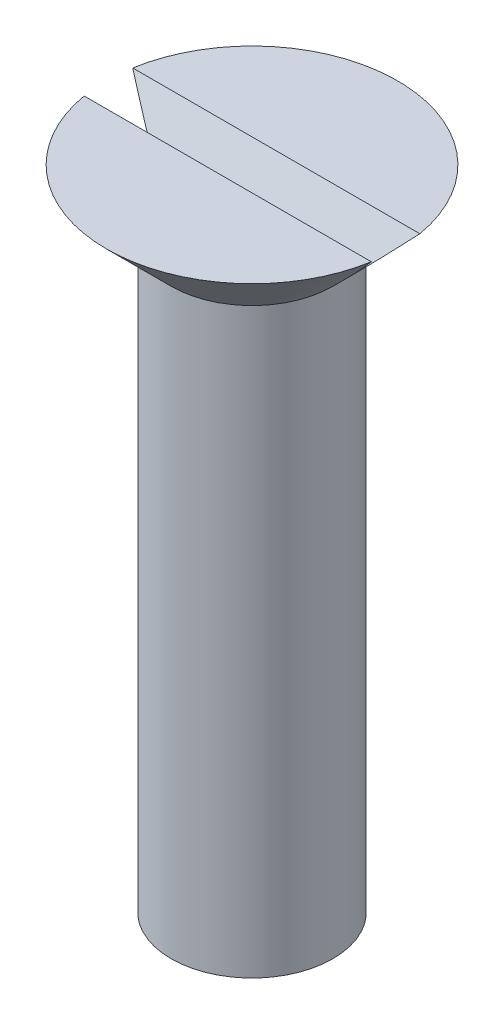
SolidWorks part; units mm, degrees
ref_plane "Front Plane" through (0, 0, 0) normal (0, 0, 1) x (1, 0, 0)
ref_plane "Top Plane" through (0, 0, 0) normal (0, 1, 0) x (1, 0, 0)
ref_plane "Right Plane" through (0, 0, 0) normal (1, 0, 0) x (0, 0, -1)
sketch "Sketch1" plane through (0, 0, 0) normal (0, 0, 1) x (1, 0, 0)
  line L0 (0, 45.5211) -> (0, -52.2099) construction
  line L1 (0, 35.1163) -> (4.5, 35.1163)
  line L2 (4.5, 35.1163) -> (2.5, 33.1163)
  line L3 (2.5, 33.1163) -> (2.5, 15.1163)
  line L4 (2.5, 15.1163) -> (0, 15.1163)
  line L5 (0, 35.1163) -> (0, 15.1163)
  dimension "D1" = 135
  dimension "D2" = 2.5
  dimension "D3" = 4.5
  dimension "D4" = 18
revolve "Revolve1" add sketch "Sketch1" angle 360 about L0
sketch "Sketch2" plane through (0, 0, 0) normal (1, 0, 0) x (0, 0, -1)
  line L0 (0, 35.9281) -> (0, 33.9586) construction
  line L1 (-0.75, 35.1163) -> (0, 33.6163)
  line L2 (4.5, 35.1163) -> (-4.5, 35.1163) construction
  line L3 (0, 33.6163) -> (0.75, 35.1163)
  line L4 (-0.75, 35.1163) -> (0.75, 35.1163)
  dimension "D1" = 1.5
  dimension "D2" = 1.5
  dimension "D3" = 0.75
extrude "Extrude1" cut sketch "Sketch2" against normal mid plane 10
